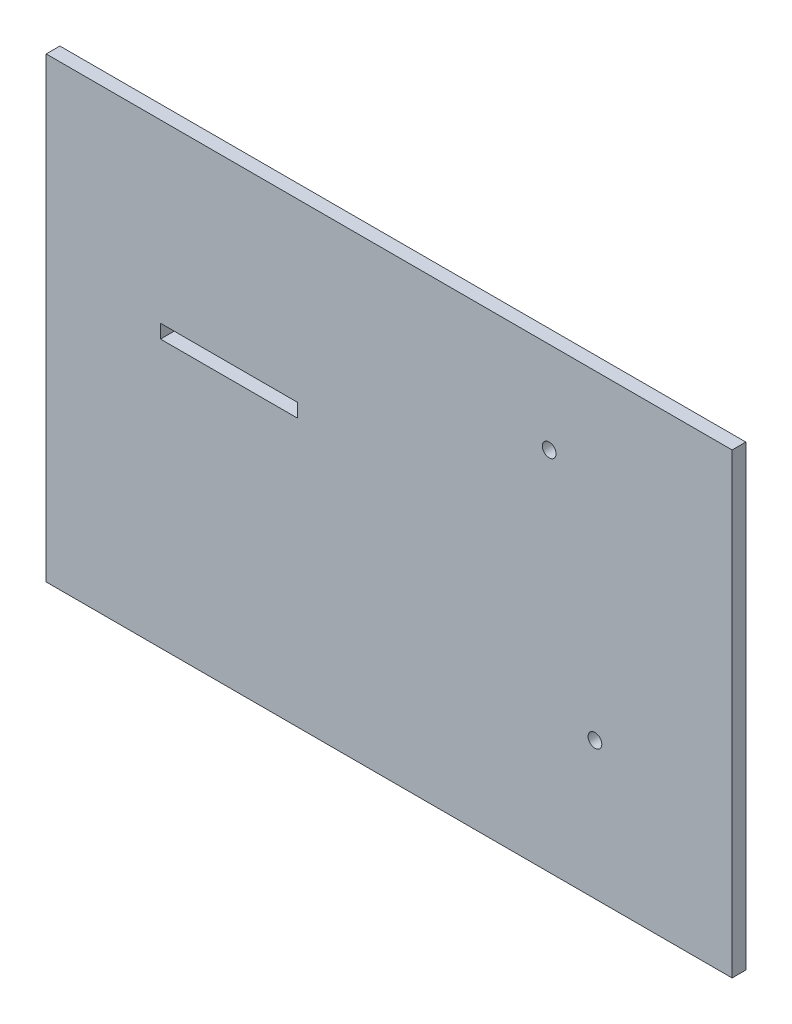
SolidWorks part; units mm, degrees
ref_plane "前视基准面" through (0, 0, 0) normal (0, 0, 1) x (1, 0, 0)
ref_plane "上视基准面" through (0, 0, 0) normal (0, 1, 0) x (1, 0, 0)
ref_plane "右视基准面" through (0, 0, 0) normal (1, 0, 0) x (0, 0, -1)
sketch "草图1" plane through (0, 0, 0) normal (0, 0, 1) x (1, 0, 0)
  line L1 (0, 0) -> (-150, 0)
  line L2 (0, 0) -> (0, 100)
  line L3 (0, 100) -> (-150, 100)
  line L4 (-150, 0) -> (-150, 100)
  dimension "D1" = 150
  dimension "D2" = 100
extrude "凸台-拉伸2" add sketch "草图1" along normal blind 3
sketch "草图2" plane through (0, 0, 3) normal (0, 0, 1) x (1, 0, 0)
  line L0 (0, 0) -> (0, 100) construction
  line L1 (-150, 0) -> (0, 0) construction
  circle A0 centre (-30, 30) radius 1.5
  circle A1 centre (-40, 80) radius 1.5
  dimension "D1" = 3
  dimension "D3" = 30
  dimension "D4" = 10
  dimension "D5" = 50
  dimension "D2" = 30
extrude "切除-拉伸1" cut sketch "草图2" against normal through all
sketch "草图3" plane through (0, 0, 3) normal (0, 0, 1) x (1, 0, 0)
  line L0 (-153.5012, 64) -> (-40.7773, 64) construction
  line L1 (-110, 69.5) -> (-110, 66.5) construction
  line L2 (-129.6551, 66.5) -> (-106.4736, 66.5) construction
  line L3 (-129.6551, 66.5) -> (-129.6551, 61.5) construction
  line L4 (-129.6551, 61.5) -> (-106.4736, 61.5) construction
  line L5 (-106.4736, 66.5) -> (-106.4736, 61.5) construction
  line L6 (-125, 69.5) -> (-95, 69.5) construction
  line L7 (-125, 69.5) -> (-125, 66.5) construction
  line L8 (-125, 66.5) -> (-95, 66.5) construction
  line L9 (-95, 69.5) -> (-95, 66.5) construction
  line L10 (-125, 61.5) -> (-95, 61.5)
  line L11 (-95, 58.5) -> (-95, 61.5)
  line L12 (-125, 58.5) -> (-95, 58.5)
  line L13 (-125, 58.5) -> (-125, 61.5)
  line L14 (-135.674, 60) -> (-85.1798, 60) construction
  circle A0 centre (-30, 30) radius 1.5 construction
  dimension "D1" = 30
  dimension "D2" = 5
  dimension "D3" = 3
  dimension "D4" = 30
  dimension "D5" = 80
extrude "切除-拉伸2" cut sketch "草图3" against normal through all
